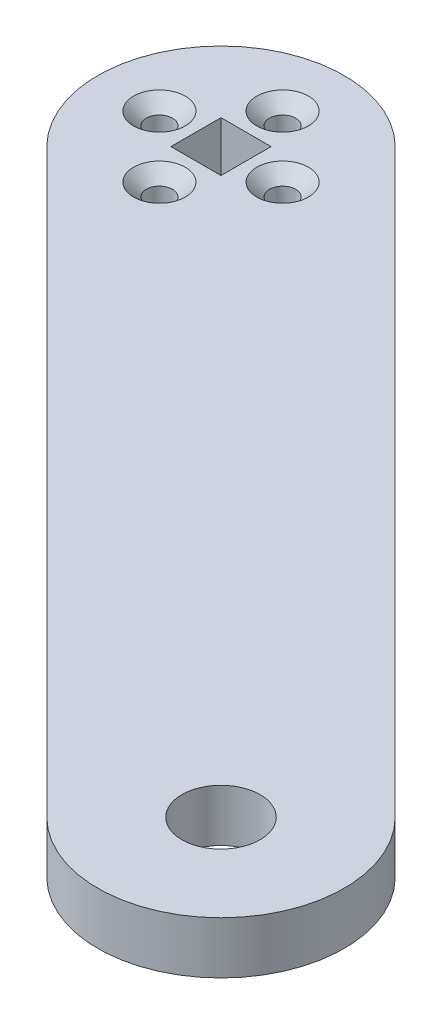
SolidWorks part; units mm, degrees
ref_plane "Front Plane" through (0, 0, 0) normal (0, 0, 1) x (1, 0, 0)
ref_plane "Top Plane" through (0, 0, 0) normal (0, 1, 0) x (1, 0, 0)
ref_plane "Right Plane" through (0, 0, 0) normal (1, 0, 0) x (0, 0, -1)
sketch "Sketch2" plane through (0, 0, 0) normal (0, 1, 0) x (1, 0, 0)
  line L0 (0, 0) -> (70.7107, -70.7107) construction
  line L1 (-3.05, 3.05) -> (3.05, 3.05)
  line L2 (-3.05, 3.05) -> (-3.05, -3.05)
  line L3 (-3.05, -3.05) -> (3.05, -3.05)
  line L4 (3.05, 3.05) -> (3.05, -3.05)
  line L5 (0, 0) -> (70.7107, 0) construction
  line L6 (-10.6066, -10.6066) -> (10.6066, 10.6066) construction
  line L7 (10.6066, 10.6066) -> (81.3173, -60.1041)
  line L8 (-10.6066, -10.6066) -> (60.1041, -81.3173)
  circle A0 centre (70.7107, -70.7107) radius 4.7625
  arc A1 (10.6066, 10.6066) -> (-10.6066, -10.6066) centre (0, 0) ccw
  arc A2 (81.3173, -60.1041) -> (60.1041, -81.3173) centre (70.7107, -70.7107) cw
  circle A3 centre (0, 7.5) radius 1.5 construction
  circle A4 centre (-7.5, 0) radius 1.5 construction
  circle A5 centre (0, 0) radius 7.5 construction
  circle A8 centre (70.7107, -70.7107) radius 37 construction
  circle A9 centre (7.5, 0) radius 1.5 construction
  circle A10 centre (0, -7.5) radius 1.5 construction
  point P4 (0, 3.05)
  point P6 (3.05, 0)
  point P13 (0, 0)
  dimension "D4" = 9.525
  dimension "D5" = 15
  dimension "D6" = 15
  dimension "D7" = 3
  dimension "D8" = 15
  dimension "D9" = 74
  dimension "D1" = 6.1
  dimension "D2" = 45
  dimension "D3" = 100
extrude "Boss-Extrude1" add sketch "Sketch2" against normal blind 6.35 contours A1 L8 A2 L7
hole_wizard "CSK for M3 Flat Head Machine Screw1" positions "3DSketch1" profile "Sketch3" countersink size "M3" standard "ANSI Metric" end condition up to next
sketch3d "3DSketch1"
  point P0 (0, 0, -7.5)
  point P2 (-7.5, 0, 0)
  point P4 (7.5, 0, 0)
  point P13 (0, 0, 7.5)
sketch "Sketch3" plane through (0, 0, -7.5) normal (1, 0, 0) x (0, 0, 1)
  line L0 (0, 0) -> (0, 6.35)
  line L1 (0, 6.35) -> (1.6, 6.35)
  line L2 (1.6, 6.35) -> (1.6, 1.55)
  line L3 (1.6, 1.55) -> (3.15, 0)
  line L5 (3.15, 0) -> (0, 0)
  line L6 (-1.6, 1.55) -> (-3.15, 0) construction
  line L11 (0, -6.35) -> (0, 107.95) construction
  dimension "Thru Hole Dia." = 3.2
  dimension "Thru Hole Depth" = 6.35
  dimension "Near C'Sink Dia." = 6.3
  dimension "Near C'Sink Angle" = 90
